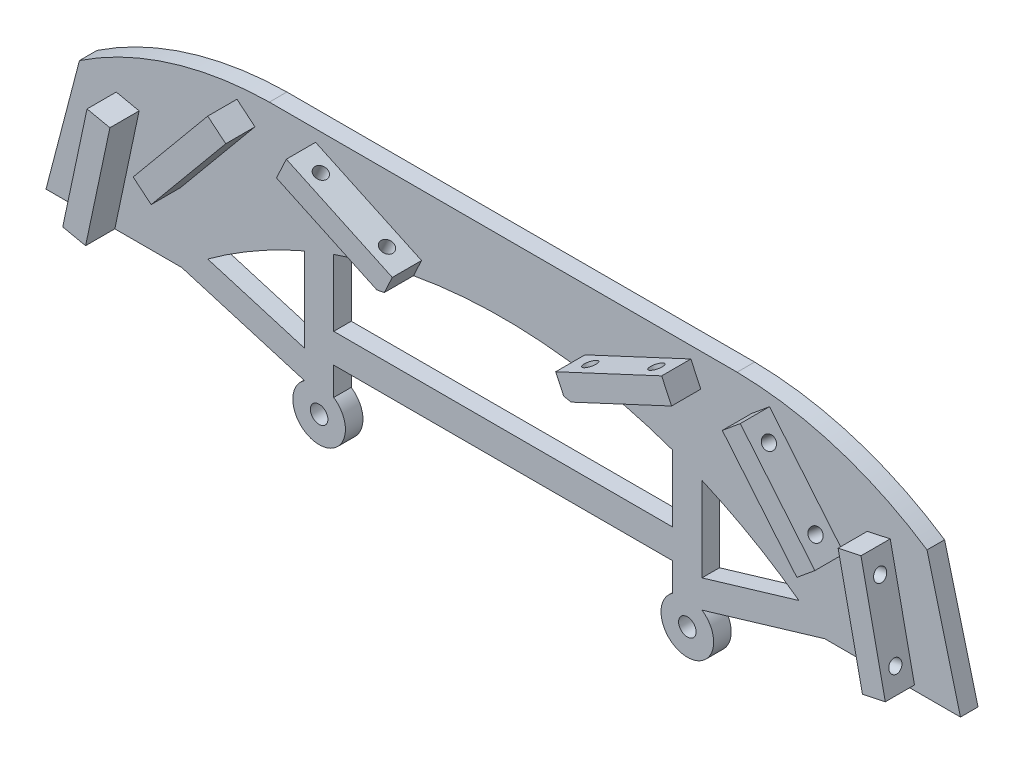
SolidWorks part; units mm, degrees
ref_plane "Płaszczyzna przednia" through (0, 0, 0) normal (0, 0, 1) x (1, 0, 0)
ref_plane "Płaszczyzna górna" through (0, 0, 0) normal (0, 1, 0) x (1, 0, 0)
ref_plane "Płaszczyzna prawa" through (0, 0, 0) normal (1, 0, 0) x (0, 0, -1)
sketch "Szkic1" plane through (0, 0, 0) normal (0, 0, 1) x (1, 0, 0)
  line L0 (0, 0) -> (90, 0)
  line L1 (0, 0) -> (-90, 0)
  line L2 (-40, 30) -> (40, 30)
  line L3 (0, 59.0718) -> (0, -13.5985) construction
  arc A0 (-90, 0) -> (-40, 30) centre (-39.2, -28) cw
  arc A1 (40, 30) -> (90, 0) centre (39.2, -28) cw
  dimension "D1" = 90
  dimension "D2" = 90
  dimension "D3" = 30
  dimension "D4" = 40
  dimension "D5" = 40
  dimension "D6" = 58
  dimension "D7" = 58
extrude "Dodanie-wyciągnięcie1" add sketch "Szkic1" along normal blind 3
sketch "Szkic2" plane through (0, 0, 3) normal (0, 0, 1) x (1, 0, 0)
  line L0 (-61.8718, 21.5486) -> (-66.4521, 0)
  line L1 (-66.4521, 0) -> (-62.2939, 19.563)
  line L2 (-66.4521, 0) -> (-70.3647, 0.8316)
  line L3 (-62.2939, 19.563) -> (-66.2065, 20.3946)
  line L4 (-70.3647, 0.8316) -> (-66.2065, 20.3946)
  line L5 (-90, 0) -> (90, 0) construction
  line L6 (0, 36.2463) -> (0, -15.7946) construction
  line L11 (-52.7959, 14.6485) -> (-30.3432, 41.7466) construction
  line L12 (-55.2358, 11.7038) -> (-42.4755, 27.1042)
  line L13 (-55.2358, 11.7038) -> (-58.3159, 14.2558)
  line L14 (-42.4755, 27.1042) -> (-45.5556, 29.6563)
  line L15 (-58.3159, 14.2558) -> (-45.5556, 29.6563)
  line L16 (15.669, 17.9224) -> (33.7952, 26.3748) construction
  line L17 (15.669, 17.9224) -> (33.7952, 26.3748)
  line L18 (15.669, 17.9224) -> (13.9786, 21.5476)
  line L19 (33.7952, 26.3748) -> (32.1047, 30)
  line L20 (13.9786, 21.5476) -> (32.1047, 30)
  line L21 (40, 30) -> (-40, 30) construction
  line L22 (62.2939, 19.563) -> (66.2065, 20.3946)
  line L23 (70.3647, 0.8316) -> (66.2065, 20.3946)
  line L24 (66.4521, 0) -> (70.3647, 0.8316)
  line L25 (66.4521, 0) -> (62.2939, 19.563)
  line L26 (42.4755, 27.1042) -> (45.5556, 29.6563)
  line L27 (58.3159, 14.2558) -> (45.5556, 29.6563)
  line L28 (55.2358, 11.7038) -> (58.3159, 14.2558)
  line L29 (55.2358, 11.7038) -> (42.4755, 27.1042)
  line L30 (-33.7952, 26.3748) -> (-32.1047, 30)
  line L31 (-13.9786, 21.5476) -> (-32.1047, 30)
  line L32 (-15.669, 17.9224) -> (-13.9786, 21.5476)
  line L33 (-15.669, 17.9224) -> (-33.7952, 26.3748)
  arc A1 (-40, 30) -> (-90, 0) centre (-39.2, -28) ccw construction
  point P2 (36.2881, 26.3748)
  point P5 (12.1091, 17.9224)
  point P24 (-20.5814, 30)
  dimension "D1" = 20
  dimension "D2" = 4
  dimension "D3" = 65
  dimension "D4" = 4
  dimension "D5" = 20
  dimension "D6" = 50
  dimension "D7" = 50.356
  dimension "D8" = 78
  dimension "D9" = 4
  dimension "D10" = 20
  dimension "D11" = 25
extrude "Dodanie-wyciągnięcie2" add sketch "Szkic2" along normal blind 5 contours L25 L24 L23 L22 | L29 L28 L27 L26 | L20 L18 L17 L19 | L33 L32 L31 L30 | L15 L13 L12 L14 | L4 L2 L0 L3
sketch "Szkic4" plane through (67.4922, 14.3459, 0) normal (0.9781, 0.2079, 0) x (0, 0, -1)
  line L1 (-5.5, 6.1838) -> (-5.5, -13.8162) construction
  line L2 (-8, 6.1838) -> (-3, 6.1838) construction
  line L3 (-8, -13.8162) -> (-3, -13.8162) construction
  circle A0 centre (-5.5, 2.4338) radius 1.1
  circle A1 centre (-5.5, -10.0662) radius 1.1
  point P12 (-5.5, -3.8162)
  dimension "D2" = 2.2
  dimension "D3" = 2.2
  dimension "D4" = 12.5
  dimension "D5" = 6.25
extrude "Wytnij-wyciągnięcie1" cut sketch "Szkic4" against normal blind 5
sketch "Szkic5" plane through (41.5812, 34.4529, 0) normal (0.77, 0.638, 0) x (0, 0, -1)
  line L0 (-5.5, -6.2293) -> (-5.5, -26.2293) construction
  line L1 (-8, -6.2293) -> (-3, -6.2293) construction
  line L2 (-8, -26.2293) -> (-3, -26.2293) construction
  circle A0 centre (-5.5, -9.9793) radius 1.1
  circle A1 centre (-5.5, -22.4793) radius 1.1
  point P8 (-5.5, -26.2293)
  point P11 (-5.5, -16.2293)
  dimension "D3" = 2.2
  dimension "D4" = 2.2
  dimension "D1" = 12.5
  dimension "D2" = 6.25
extrude "Wytnij-wyciągnięcie2" cut sketch "Szkic5" against normal blind 5
sketch "Szkic7" plane through (0, 0, 3) normal (0, 0, 1) x (1, 0, 0)
  line L0 (-78.2261, 0) -> (-71.3957, 20.2501)
  line L1 (-90, 0) -> (-66.4521, 0) construction
  line L2 (78.2261, 0) -> (71.3957, 20.2501)
  line L3 (66.4521, 0) -> (90, 0) construction
  line L4 (71.3957, 20.2501) -> (90, 20.2501)
  line L5 (90, 20.2501) -> (90, 0)
  line L6 (90, 0) -> (78.2261, 0)
  line L7 (-90, 0) -> (-90, 20.2501)
  line L8 (-90, 20.2501) -> (-71.3957, 20.2501)
  line L9 (-78.2261, 0) -> (-90, 0)
  arc A0 (-45.5556, 29.6563) -> (-90, 0) centre (-39.2, -28) ccw construction
  arc A1 (90, 0) -> (45.5556, 29.6563) centre (39.2, -28) ccw construction
extrude "Wytnij-wyciągnięcie4" cut sketch "Szkic7" against normal up to surface (3 mm away) up to face at (0, 18.3697, 0)
sketch "Szkic8" plane through (0, 0, 3) normal (0, 0, 1) x (1, 0, 0)
  line L0 (-55, -6.9177) -> (-55, 6.9177) construction
  line L1 (55, 6.8189) -> (55, -5.6262) construction
  line L2 (-66.4521, 0) -> (66.4521, 0) construction
  line L3 (-55, 0) -> (55, 0)
  arc A0 (-55, 0) -> (55, 0) centre (0, -65.625) cw
  dimension "D3" = 20
  dimension "D1" = 55
  dimension "D2" = 55
extrude "Wytnij-wyciągnięcie5" cut sketch "Szkic8" against normal blind 5
sketch "Szkic9" plane through (0, 0, 3) normal (0, 0, 1) x (1, 0, 0)
  line L0 (-66.4521, 0) -> (-55, 0) construction
  line L2 (-34, -1.46) -> (-34, 16.8993)
  line L3 (-29, -6.2583) -> (-29, -1.4573)
  line L4 (-34, 16.8993) -> (-29, 16.8993)
  line L6 (29, -6.2583) -> (29, -1.4573)
  line L7 (34, -1.4846) -> (34, 16.7067)
  line L8 (29, 16.7067) -> (34, 16.7067)
  line L9 (-29, -1.4573) -> (29, -1.4573)
  line L12 (-29, 3.5427) -> (29, 3.5427)
  line L13 (-29, 3.5427) -> (-29, 16.8993)
  line L14 (29, 3.5427) -> (29, 16.7067)
  line L16 (-34, -1.46) -> (-55, 4.7983)
  line L17 (-34, -6.2583) -> (-55, 0)
  line L18 (-55, 4.7983) -> (-55, 0)
  line L20 (34, -1.4846) -> (55, 4.7737)
  line L21 (34, -6.2583) -> (55, 0)
  line L22 (55, 4.7737) -> (55, 0)
  circle A0 centre (-31.5, -10) radius 1.5
  circle A1 centre (31.5, -10) radius 1.5
  arc A2 (-34, -6.2583) -> (-29, -6.2583) centre (-31.5, -10) ccw
  arc A3 (29, -6.2583) -> (34, -6.2583) centre (31.5, -10) ccw
  dimension "D2" = 3
  dimension "D5" = 3
  dimension "D6" = 9
  dimension "D7" = 9
  dimension "D1" = 10
  dimension "D3" = 31.5
  dimension "D4" = 31.5
  dimension "D8" = 5
  dimension "D9" = 2.5
  dimension "D10" = 5
  dimension "D11" = 5
extrude "Dodanie-wyciągnięcie3" add sketch "Szkic9" against normal up to surface (3 mm away) up to face at (0, 15.6302, 0)
sketch "Szkic10" plane through (-5.7566, 12.345, 0) normal (-0.4226, 0.9063, 0) x (0.9063, 0.4226, 0)
  line L0 (21.7753, -5.5) -> (41.7753, -5.5) construction
  line L1 (21.7753, -8) -> (21.7753, -3) construction
  line L2 (41.7753, -8) -> (41.7753, -3) construction
  circle A0 centre (25.5253, -5.5) radius 1.1
  circle A1 centre (38.0253, -5.5) radius 1.1
  point P10 (31.7753, -5.5)
  dimension "D3" = 2.2
  dimension "D4" = 2.2
  dimension "D1" = 12.5
  dimension "D2" = 6.25
extrude "Wytnij-wyciągnięcie6" cut sketch "Szkic10" against normal blind 5
mirror "Lustro3" about plane through (0, 0, 0) normal (1, 0, 0) of "Wytnij-wyciągnięcie6"
sketch "Szkic11" plane through (0, 0, 3) normal (0, 0, -1) x (-1, 0, 0)
  line L4 (15.3468, 18.6135) -> (15.669, 17.9224)
  line L5 (15.669, 17.9224) -> (16.6285, 18.3698)
  line L6 (15.3468, 18.6135) -> (15.669, 17.9224)
  line L7 (15.669, 17.9224) -> (16.6285, 18.3698)
  arc A2 (16.6285, 18.3698) -> (15.3468, 18.6135) centre (0, -65.625) ccw
  arc A3 (16.6285, 18.3698) -> (15.3468, 18.6135) centre (0, -65.625) ccw
  dimension "D1" = 0
extrude "Wytnij-wyciągnięcie7" cut sketch "Szkic11" against normal blind 5
mirror "Lustro4" about plane through (0, 0, 0) normal (1, 0, 0) of "Wytnij-wyciągnięcie7"
sketch "Szkic13" plane through (0, 0, 0) normal (0, 0, -1) x (-1, 0, 0)
  line L4 (-78.2261, 0) -> (-72.5058, 21.9138)
  line L5 (40.0137, 32) -> (-40.0137, 32)
  line L6 (40.0137, 32) -> (-40.0137, 32)
  line L7 (72.5058, 21.9138) -> (78.2261, 0)
  line L8 (78.2261, 0) -> (0, 30)
  line L9 (-40, 30) -> (40, 30) construction
  line L10 (0, 30) -> (-78.2261, 0)
  arc A10 (72.5058, 21.9138) -> (40.0137, 32) centre (39.2, -28) ccw
  arc A11 (-40.0137, 32) -> (-72.5058, 21.9138) centre (-39.2, -28) ccw
  arc A12 (72.5058, 21.9138) -> (40.0137, 32) centre (39.2, -28) ccw
  arc A13 (-40.0137, 32) -> (-72.5058, 21.9138) centre (-39.2, -28) ccw
  dimension "D1" = 2
extrude "Dodanie-wyciągnięcie4" add sketch "Szkic13" against normal up to surface (3 mm away) up to face at (-39.6095, 5.1465, 3)
